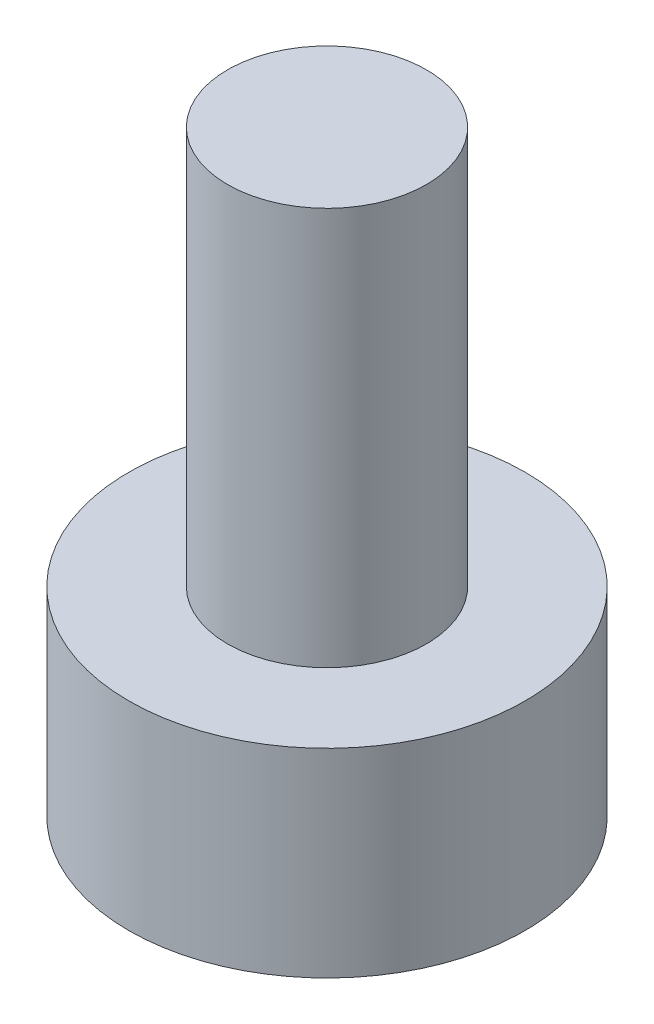
SolidWorks part; units mm, degrees
ref_plane "Front Plane" through (0, 0, 0) normal (0, 0, 1) x (1, 0, 0)
ref_plane "Top Plane" through (0, 0, 0) normal (0, 1, 0) x (1, 0, 0)
ref_plane "Right Plane" through (0, 0, 0) normal (1, 0, 0) x (0, 0, -1)
sketch "Sketch1" plane through (0, 0, 0) normal (0, 1, 0) x (1, 0, 0)
  circle A0 centre (0, 0) radius 4.98
  dimension "D1" = 9.96
extrude "Boss-Extrude1" add sketch "Sketch1" along normal blind 5
sketch "Sketch2" plane through (0, 5, 0) normal (0, 1, 0) x (1, 0, 0)
  circle A0 centre (0, 0) radius 2.5
  dimension "D1" = 5
extrude "Boss-Extrude2" add sketch "Sketch2" along normal blind 10
